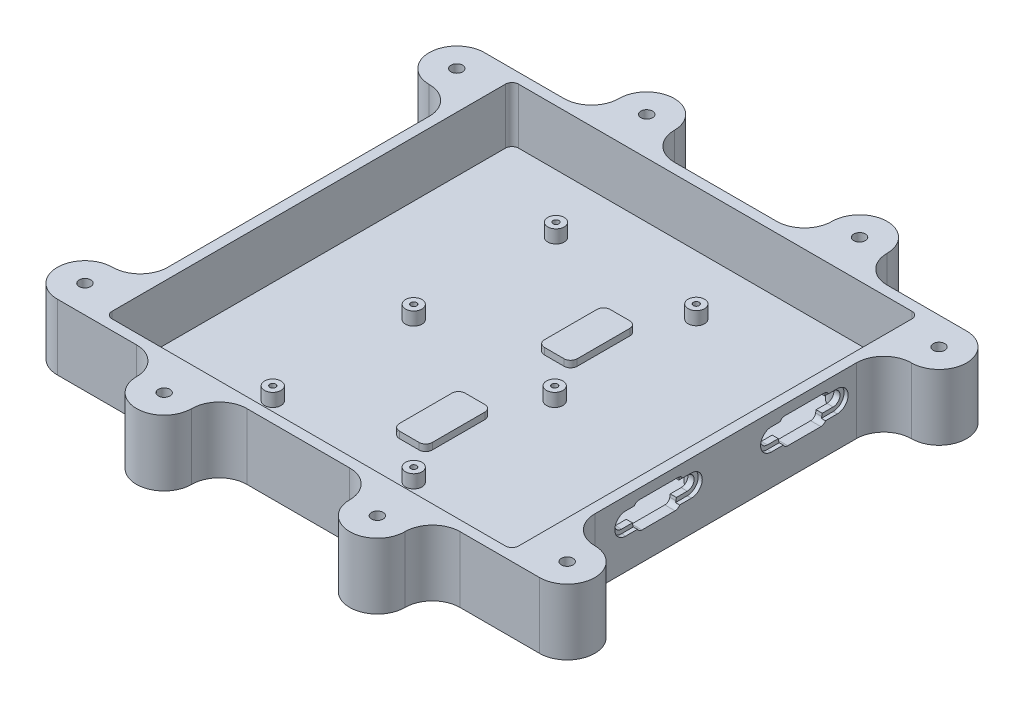
SolidWorks part; units mm, degrees
material "6061-T6 (SS)"
ref_plane "Front Plane" through (0, 0, 0) normal (0, 0, 1) x (1, 0, 0)
ref_plane "Top Plane" through (0, 0, 0) normal (0, 1, 0) x (1, 0, 0)
ref_plane "Right Plane" through (0, 0, 0) normal (1, 0, 0) x (0, 0, -1)
sketch "Sketch1" plane through (0, 0, 0) normal (0, 1, 0) x (1, 0, 0)
  line L1 (0, 0) -> (165.1, 0)
  line L2 (0, 0) -> (0, 165.1)
  line L3 (0, 165.1) -> (165.1, 165.1)
  line L4 (165.1, 0) -> (165.1, 165.1)
  dimension "D1" = 165.1
  dimension "D2" = 165.1
extrude "Boss-Extrude1" add sketch "Sketch1" along normal blind 25.4
shell "Shell1" thickness 3.9624
sketch "Sketch4" plane through (0, 3.9624, 0) normal (0, 1, 0) x (1, 0, 0)
  line L0 (161.1376, 3.9624) -> (161.1376, 161.1376) construction
  line L1 (161.1376, 161.1376) -> (3.9624, 161.1376) construction
  line L2 (161.1376, 161.1376) -> (3.9624, 161.1376) construction
  circle A18 centre (43.5892, 29.022) radius 3.175
  circle A19 centre (98.0872, 29.022) radius 3.175
  circle A20 centre (152.588, 29.022) radius 3.175
  circle A21 centre (152.588, 83.5228) radius 3.175
  circle A22 centre (43.5892, 83.5228) radius 3.175
  circle A23 centre (98.0872, 83.5228) radius 3.175
  circle A24 centre (152.588, 138.2725) radius 3.175
  circle A25 centre (98.0872, 138.2725) radius 3.175
  circle A26 centre (43.5892, 138.524) radius 3.175
  dimension "D4" = 54.7497
  dimension "D5" = 54.5008
  dimension "D7" = 6.35
  dimension "D1" = 8.5496
  dimension "D2" = 22.8651
  dimension "D3" = 109.2505
  dimension "D6" = 108.999
  dimension "D8" = 22.6136
extrude "Boss-Extrude2" add sketch "Sketch4" along normal blind 5.08
fillet "Fillet1" radius 2.54 4 edges at (3.9624, 14.6812, -3.9624) (161.1376, 14.6812, -3.9624) (161.1376, 14.6812, -161.1376) (3.9624, 14.6812, -161.1376)
sketch "Sketch5" plane through (0, 0, 0) normal (0, -1, 0) x (1, 0, 0)
  line L0 (82.55, -165.1) -> (82.55, 0) construction
  line L9 (165.1, -165.1) -> (0, -165.1) construction
  line L10 (0, 0) -> (165.1, 0) construction
  line L19 (175.768, 0) -> (165.1, 0)
  line L20 (-10.668, 0) -> (0, 0)
  line L21 (0, -165.1) -> (0, 0) construction
  line L23 (0, -82.55) -> (44.7871, -82.55) construction
  line L40 (-10.668, -165.1) -> (0, -165.1)
  line L41 (175.768, -165.1) -> (165.1, -165.1)
  line L68 (0, 0) -> (-10.668, 0)
  line L75 (165.1, -165.1) -> (0, -165.1) construction
  line L88 (0, 0) -> (165.1, 0) construction
  line L89 (19.939, 0) -> (62.611, 0)
  line L90 (102.362, 0) -> (145.034, 0)
  line L91 (165.1, 0) -> (165.1, -165.1) construction
  line L92 (165.1, 0) -> (165.1, -32.004)
  line L93 (165.1, -133.096) -> (165.1, -165.1)
  line L94 (145.034, -165.1) -> (102.362, -165.1)
  line L95 (62.738, -165.1) -> (20.066, -165.1)
  line L96 (0, -133.096) -> (0, -165.1)
  line L97 (0, 0) -> (0, -32.004)
  arc A24 (51.943, 10.668) -> (62.611, 0) centre (62.611, 10.668) ccw
  arc A25 (30.607, 10.668) -> (19.939, 0) centre (19.939, 10.668) cw
  arc A26 (51.943, 10.668) -> (41.275, 21.336) centre (41.275, 10.668) ccw
  arc A27 (41.275, 21.336) -> (30.607, 10.668) centre (41.275, 10.668) ccw
  arc A28 (113.03, 10.668) -> (102.362, 0) centre (102.362, 10.668) cw
  arc A29 (134.366, 10.668) -> (145.034, 0) centre (145.034, 10.668) ccw
  arc A30 (134.366, 10.668) -> (123.698, 21.336) centre (123.698, 10.668) ccw
  arc A31 (123.698, 21.336) -> (113.03, 10.668) centre (123.698, 10.668) ccw
  arc A32 (165.1, -32.004) -> (175.768, -21.336) centre (175.768, -32.004) cw
  arc A33 (175.768, -21.336) -> (175.768, 0) centre (175.768, -10.668) ccw
  arc A34 (165.1, -133.096) -> (175.768, -143.764) centre (175.768, -133.096) ccw
  arc A35 (175.768, -143.764) -> (175.768, -165.1) centre (175.768, -154.432) cw
  arc A36 (145.034, -165.1) -> (134.366, -175.768) centre (145.034, -175.768) ccw
  arc A37 (113.03, -175.768) -> (102.362, -165.1) centre (102.362, -175.768) ccw
  arc A38 (134.366, -175.768) -> (113.03, -175.768) centre (123.698, -175.768) cw
  arc A39 (62.738, -165.1) -> (52.07, -175.768) centre (62.738, -175.768) ccw
  arc A40 (30.734, -175.768) -> (20.066, -165.1) centre (20.066, -175.768) ccw
  arc A41 (52.07, -175.768) -> (30.734, -175.768) centre (41.402, -175.768) cw
  arc A42 (0, -133.096) -> (-10.668, -143.764) centre (-10.668, -133.096) cw
  arc A43 (-10.668, -143.764) -> (-10.668, -165.1) centre (-10.668, -154.432) ccw
  arc A44 (0, -32.004) -> (-10.668, -21.336) centre (-10.668, -32.004) ccw
  arc A45 (-10.668, -21.336) -> (-10.668, 0) centre (-10.668, -10.668) cw
  dimension "D5" = 10.668
  dimension "D8" = 41.402
  dimension "D4" = 41.275
  dimension "D9" = 10.668
  dimension "D10" = 10.668
  dimension "D6" = 42.672
  dimension "D13" = 42.672
  dimension "D3" = 10.668
  dimension "D7" = 10.668
  dimension "D14" = 10.668
  dimension "D15" = 10.668
  dimension "D16" = 10.668
  dimension "D18" = 10.668
  dimension "D12" = 10.668
  dimension "D1" = 0
  dimension "D11" = 41.402
  dimension "D17" = 10.668
  dimension "D19" = 10.668
  dimension "D20" = 41.402
  dimension "D21" = 10.668
extrude "Boss-Extrude3" add sketch "Sketch5" against normal blind 25.4
sketch "Sketch25" plane through (0, 3.9624, 0) normal (0, 1, 0) x (1, 0, 0)
  line L0 (0, 82.55) -> (165.1, 82.55) construction
  line L1 (0, 133.096) -> (0, 32.004) construction
  line L2 (165.1, 32.004) -> (165.1, 133.096) construction
ref_plane "Plane1" through (0, 0, -82.55) normal (0, 0, 1) x (1, 0, 0)
sketch "Sketch77" plane through (0, 3.9624, 0) normal (0, 1, 0) x (1, 0, 0)
  line L0 (3.9624, 158.5976) -> (3.9624, 6.5024) construction
  line L1 (78.1787, 66.2508) -> (90.8787, 66.2508)
  line L2 (78.1787, 66.2508) -> (78.1787, 40.8508)
  line L3 (78.1787, 40.8508) -> (90.8787, 40.8508)
  line L4 (90.8787, 66.2508) -> (90.8787, 40.8508)
  line L5 (78.1787, 122.301) -> (90.8787, 122.301)
  line L6 (78.1787, 122.301) -> (78.1787, 96.901)
  line L7 (78.1787, 96.901) -> (90.8787, 96.901)
  line L8 (90.8787, 122.301) -> (90.8787, 96.901)
  line L9 (6.5024, 3.9624) -> (158.5976, 3.9624) construction
  line L10 (158.5976, 161.1376) -> (6.5024, 161.1376) construction
  dimension "D2" = 12.7
  dimension "D3" = 0
  dimension "D4" = 0
  dimension "D5" = 74.2163
  dimension "D6" = 25.4
  dimension "D7" = 38.8366
  dimension "D8" = 30.6502
  dimension "D9" = 36.8884
sketch "Sketch78" [suppressed] plane through (0, 0, 0) normal (0, -1, 0) x (1, 0, 0)
  line L11 (62.484, -165.1) -> (102.362, -165.1)
  line L12 (62.484, -165.1) -> (102.362, -165.1)
  line L13 (145.034, -165.1) -> (175.768, -165.1)
  line L14 (145.034, -165.1) -> (175.768, -165.1)
  line L15 (102.362, 0) -> (62.611, 0)
  line L16 (102.362, 0) -> (62.611, 0)
  line L17 (165.1, -133.096) -> (165.1, -32.004)
  line L18 (19.939, 0) -> (-10.668, 0)
  line L19 (19.939, 0) -> (-10.668, 0)
  line L23 (0, -32.004) -> (0, -133.096)
  line L29 (165.1, -133.096) -> (165.1, -32.004)
  line L35 (0, -32.004) -> (0, -133.096)
  line L54 (-10.668, -165.1) -> (19.812, -165.1)
  line L55 (-10.668, -165.1) -> (19.812, -165.1)
  line L82 (175.768, 0) -> (145.034, 0)
  arc A3 (51.943, 10.668) -> (62.611, 0) centre (62.611, 10.668) ccw
  arc A4 (51.943, 10.668) -> (62.611, 0) centre (62.611, 10.668) ccw
  arc A5 (51.943, 10.668) -> (30.607, 10.668) centre (41.275, 10.668) ccw
  arc A6 (51.943, 10.668) -> (30.607, 10.668) centre (41.275, 10.668) ccw
  arc A7 (19.939, 0) -> (30.607, 10.668) centre (19.939, 10.668) ccw
  arc A8 (19.939, 0) -> (30.607, 10.668) centre (19.939, 10.668) ccw
  arc A32 (-10.668, -143.764) -> (0, -133.096) centre (-10.668, -133.096) ccw
  arc A33 (-10.668, -143.764) -> (0, -133.096) centre (-10.668, -133.096) ccw
  arc A34 (-10.668, -143.764) -> (-10.668, -165.1) centre (-10.668, -154.432) ccw
  arc A35 (-10.668, -143.764) -> (-10.668, -165.1) centre (-10.668, -154.432) ccw
  arc A36 (30.48, -175.768) -> (19.812, -165.1) centre (19.812, -175.768) ccw
  arc A37 (30.48, -175.768) -> (19.812, -165.1) centre (19.812, -175.768) ccw
  arc A38 (30.48, -175.768) -> (51.816, -175.768) centre (41.148, -175.768) ccw
  arc A39 (30.48, -175.768) -> (51.816, -175.768) centre (41.148, -175.768) ccw
  arc A40 (62.484, -165.1) -> (51.816, -175.768) centre (62.484, -175.768) ccw
  arc A41 (62.484, -165.1) -> (51.816, -175.768) centre (62.484, -175.768) ccw
  arc A42 (113.03, -175.768) -> (102.362, -165.1) centre (102.362, -175.768) ccw
  arc A43 (113.03, -175.768) -> (102.362, -165.1) centre (102.362, -175.768) ccw
  arc A44 (113.03, -175.768) -> (134.366, -175.768) centre (123.698, -175.768) ccw
  arc A45 (113.03, -175.768) -> (134.366, -175.768) centre (123.698, -175.768) ccw
  arc A46 (145.034, -165.1) -> (134.366, -175.768) centre (145.034, -175.768) ccw
  arc A47 (145.034, -165.1) -> (134.366, -175.768) centre (145.034, -175.768) ccw
  arc A48 (175.768, -165.1) -> (175.768, -143.764) centre (175.768, -154.432) ccw
  arc A49 (175.768, -165.1) -> (175.768, -143.764) centre (175.768, -154.432) ccw
  arc A50 (165.1, -133.096) -> (175.768, -143.764) centre (175.768, -133.096) ccw
  arc A51 (165.1, -133.096) -> (175.768, -143.764) centre (175.768, -133.096) ccw
  arc A52 (175.768, -21.336) -> (165.1, -32.004) centre (175.768, -32.004) ccw
  arc A53 (175.768, -21.336) -> (165.1, -32.004) centre (175.768, -32.004) ccw
  arc A54 (175.768, -21.336) -> (175.768, 0) centre (175.768, -10.668) ccw
  arc A55 (175.768, -21.336) -> (175.768, 0) centre (175.768, -10.668) ccw
  arc A56 (134.366, 10.668) -> (145.034, 0) centre (145.034, 10.668) ccw
  arc A57 (134.366, 10.668) -> (145.034, 0) centre (145.034, 10.668) ccw
  arc A58 (134.366, 10.668) -> (113.03, 10.668) centre (123.698, 10.668) ccw
  arc A59 (134.366, 10.668) -> (113.03, 10.668) centre (123.698, 10.668) ccw
  arc A60 (102.362, 0) -> (113.03, 10.668) centre (102.362, 10.668) ccw
  arc A61 (102.362, 0) -> (113.03, 10.668) centre (102.362, 10.668) ccw
  arc A62 (-10.668, 0) -> (-10.668, -21.336) centre (-10.668, -10.668) ccw
  arc A63 (-10.668, 0) -> (-10.668, -21.336) centre (-10.668, -10.668) ccw
  arc A64 (0, -32.004) -> (-10.668, -21.336) centre (-10.668, -32.004) ccw
  arc A65 (0, -32.004) -> (-10.668, -21.336) centre (-10.668, -32.004) ccw
  dimension "D1" = 0
extrude "Boss-Extrude5" add sketch "Sketch77" along normal blind 2.54
sketch "Sketch83" [suppressed] plane through (165.1, 0, 0) normal (1, 0, 0) x (0, 0, -1)
  line L0 (43.5089, 25.3323) -> (43.5089, 15.6727) construction
  line L1 (43.5089, 15.6727) -> (68.5102, 15.6727) construction
  line L2 (99.5083, 15.6727) -> (124.5121, 15.6727) construction
  line L3 (106.1085, 12.9891) -> (103.4735, 18.3684)
  line L4 (48.5085, 12.4684) -> (47.4741, 18.3684)
  line L5 (61.9346, 11.1447) -> (50.0845, 11.1447)
  line L6 (64.5449, 18.3684) -> (63.5106, 12.4684)
  line L7 (49.0501, 20.2447) -> (62.969, 20.2447)
  line L12 (31.496, 25.4) -> (133.604, 25.4) construction
  line L14 (31.496, 25.4) -> (31.496, -2.54) construction
  line L15 (116.7542, 11.6654) -> (104.9041, 11.6654)
  line L20 (120.9651, 18.3684) -> (118.3302, 12.9891)
  line L21 (105.0495, 20.2447) -> (119.3892, 20.2447)
  line L22 (31.496, 25.4) -> (133.604, 25.4) construction
  line L23 (143.764, 25.4) -> (143.764, -2.54) construction
  line L24 (133.604, -2.54) -> (31.496, -2.54) construction
  circle A0 centre (43.5089, 15.6727) radius 1.7005
  circle A1 centre (68.5102, 15.6727) radius 1.7005
  arc A4 (48.5085, 12.4684) -> (50.0845, 11.1447) centre (50.0845, 12.7447) ccw
  arc A5 (61.9346, 11.1447) -> (63.5106, 12.4684) centre (61.9346, 12.7447) ccw
  arc A6 (64.5449, 18.3684) -> (62.969, 20.2447) centre (62.969, 18.6447) ccw
  arc A7 (49.0501, 20.2447) -> (47.4741, 18.3684) centre (49.0501, 18.6447) ccw
  circle A18 centre (99.5083, 15.6727) radius 1.7005
  circle A19 centre (124.5121, 15.6727) radius 1.7005
  arc A20 (106.1085, 12.9891) -> (104.9041, 11.6654) centre (106.4873, 11.4346) ccw
  arc A21 (116.7542, 11.6654) -> (118.3302, 12.9891) centre (116.7542, 13.2654) ccw
  arc A22 (120.9651, 18.3684) -> (119.3892, 20.2447) centre (119.3892, 18.6447) ccw
  arc A23 (105.0495, 20.2447) -> (103.4735, 18.3684) centre (105.0495, 18.6447) ccw
  dimension "D3" = 3.4011
  dimension "D4" = 3.4011
  dimension "D9" = 1.6
  dimension "D10" = 1.6
  dimension "D11" = 1.6
  dimension "D12" = 1.6
  dimension "D21" = 3.4011
  dimension "D25" = 1.6
  dimension "D26" = 1.6
  dimension "D27" = 1.6
  dimension "D28" = 1.6
  dimension "D38" = 4.3711
  dimension "D39" = 3.4011
  dimension "D40" = 9.7273
  dimension "D41" = 19.2519
  dimension "D43" = 15.8054
  dimension "D44" = 6.7553
  dimension "D45" = 6.7553
  dimension "D47" = 6.7553
  dimension "D49" = 15.2847
  dimension "D1" = 9.6596
  dimension "D2" = 25.0012
  dimension "D5" = 12.0129
  dimension "D6" = 3.9652
  dimension "D7" = 3.9652
  dimension "D8" = 4.572
  dimension "D13" = 5.99
  dimension "D14" = 5.99
  dimension "D15" = 13.9189
  dimension "D16" = 11.8501
  dimension "D17" = 1.8763
  dimension "D18" = 1.8763
  dimension "D19" = 1.3237
  dimension "D20" = 1.3237
  dimension "D22" = 9.7273
  dimension "D23" = 3.9652
  dimension "D24" = 4.572
  dimension "D29" = 5.99
  dimension "D30" = 5.99
  dimension "D31" = 11.8501
  dimension "D32" = 1.8763
  dimension "D33" = 1.8763
  dimension "D34" = 1.3237
  dimension "D35" = 1.3237
  dimension "D36" = 30.9982
  dimension "D37" = 0
  dimension "D42" = 14.2054
  dimension "D46" = 9.944
  dimension "D48" = 80.056
extrude "Cut-Extrude5" [suppressed] cut sketch "Sketch83" against normal blind 12.7
fillet "Fillet27" radius 2.54 8 edges at (78.1787, 5.2324, -122.301) (90.8787, 5.2324, -122.301) (78.1787, 5.2324, -96.901) (78.1787, 5.2324, -66.2508) (78.1787, 5.2324, -40.8508) (90.8787, 5.2324, -96.901) (90.8787, 5.2324, -66.2508) (90.8787, 5.2324, -40.8508)
hole_wizard "#4-40 Tapped Hole1" positions "Sketch84" profile "Sketch85" tap size "#4-40" standard "ANSI Inch"
sketch "Sketch84" plane through (0, 9.0424, 0) normal (0, 1, 0) x (1, 0, 0)
  point P0 (152.588, 29.022)
  point P3 (152.588, 83.5228)
  point P6 (152.588, 138.2725)
  point P9 (98.0872, 138.2725)
  point P12 (98.0872, 83.5228)
  point P15 (98.0872, 29.022)
  point P18 (43.5892, 29.022)
  point P21 (43.5892, 83.5228)
  point P24 (43.5892, 138.524)
cosmetic thread "Hole Thread1" parameters "D1"=5.588, "D2"=2.8448
cosmetic thread "Hole Thread2" parameters "D1"=5.588, "D2"=2.8448
cosmetic thread "Hole Thread3" parameters "D1"=5.588, "D2"=2.8448
cosmetic thread "Hole Thread4" parameters "D1"=5.588, "D2"=2.8448
cosmetic thread "Hole Thread5" parameters "D1"=5.588, "D2"=2.8448
cosmetic thread "Hole Thread6" parameters "D1"=5.588, "D2"=2.8448
cosmetic thread "Hole Thread7" parameters "D1"=5.588, "D2"=2.8448
cosmetic thread "Hole Thread8" parameters "D1"=5.588, "D2"=2.8448
cosmetic thread "Hole Thread9" parameters "D1"=5.588, "D2"=2.8448
sketch "Sketch85" plane through (152.588, 9.0424, -29.022) normal (1, 0, 0) x (0, 0, 1)
  line L0 (0, 0) -> (0, 7.0292)
  line L1 (0, 7.0292) -> (1.1303, 6.35)
  line L2 (1.1303, 6.35) -> (1.1303, 0)
  line L5 (1.1303, 0) -> (0, 0)
  line L10 (0, 7.0292) -> (-1.1303, 6.35) construction
  line L11 (0, -6.35) -> (0, 107.95) construction
  dimension "Tap Drill Dia." = 2.2606
  dimension "Tap Drill Depth" = 6.35
  dimension "Drill Angle" = 118
sketch "Sketch86" plane through (165.1, 0, 0) normal (1, 0, 0) x (0, 0, -1)
  line L0 (82.55, 25.4) -> (82.55, 0) construction
  line L1 (32.004, 25.4) -> (133.096, 25.4) construction
  line L3 (56.642, 25.4) -> (56.642, 0) construction
  line L4 (50.24, 10.8864) -> (63.044, 10.8864)
  line L6 (64.9626, 12.4963) -> (66.1463, 19.2095)
  line L7 (48.3214, 12.4963) -> (47.1377, 19.2095)
  line L8 (49.0563, 21.496) -> (64.2277, 21.496)
  line L9 (32.004, 0) -> (133.096, 0) construction
  arc A0 (49.0563, 21.496) -> (47.1377, 19.2095) centre (49.0563, 19.5478) ccw
  arc A1 (64.2277, 21.496) -> (66.1463, 19.2095) centre (64.2277, 19.5478) cw
  arc A2 (63.044, 10.8864) -> (64.9626, 12.4963) centre (63.044, 12.8346) ccw
  arc A3 (50.24, 10.8864) -> (48.3214, 12.4963) centre (50.24, 12.8346) cw
  dimension "D3" = 1.9482
  dimension "D1" = 25.908
  dimension "D2" = 6.7132
  dimension "D4" = 10
  dimension "D5" = 15.1714
  dimension "D6" = 10.8864
extrude "Cut-Extrude6" cut sketch "Sketch86" against normal up to surface (3.9624 mm away) up to face at (161.1376, 14.6812, -82.55)
sketch "Sketch87" plane through (165.1, 0, 0) normal (1, 0, 0) x (0, 0, -1)
  line L0 (43.942, 16.1912) -> (69.342, 16.1912) construction
  line L1 (43.942, 18.8582) -> (69.342, 18.8582)
  line L2 (43.942, 13.5242) -> (69.342, 13.5242)
  line L3 (64.2277, 21.496) -> (49.0563, 21.496) construction
  line L4 (50.24, 10.8864) -> (63.044, 10.8864) construction
  line L5 (56.642, 21.496) -> (56.642, 10.8864) construction
  arc A0 (43.942, 18.8582) -> (43.942, 13.5242) centre (43.942, 16.1912) ccw
  arc A1 (69.342, 13.5242) -> (69.342, 18.8582) centre (69.342, 16.1912) ccw
  point P2 (56.642, 16.1912)
  dimension "D1" = 2.667
  dimension "D2" = 25.4
extrude "Cut-Extrude7" cut sketch "Sketch87" against normal up to surface (3.9624 mm away) up to face at (161.1376, 16.0466, -56.642)
sketch "Sketch88" plane through (165.1, 0, 0) normal (1, 0, 0) x (0, 0, -1)
  line L0 (43.942, 16.1912) -> (69.342, 16.1912) construction
  line L1 (43.942, 20.4076) -> (69.342, 20.4076)
  line L2 (43.942, 11.9748) -> (69.342, 11.9748)
  line L3 (47.1997, 18.8582) -> (43.942, 18.8582) construction
  line L4 (43.942, 13.5242) -> (48.1402, 13.5242) construction
  line L5 (56.642, 21.496) -> (56.642, 10.8864) construction
  line L6 (64.2277, 21.496) -> (49.0563, 21.496) construction
  line L7 (50.24, 10.8864) -> (63.044, 10.8864) construction
  arc A0 (43.942, 20.4076) -> (43.942, 11.9748) centre (43.942, 16.1912) ccw
  arc A1 (69.342, 11.9748) -> (69.342, 20.4076) centre (69.342, 16.1912) ccw
  arc A9 (43.942, 18.8582) -> (43.942, 13.5242) centre (43.942, 16.1912) ccw construction
  point P2 (56.642, 16.1912)
  dimension "D1" = 8.4328
extrude "Cut-Extrude8" cut sketch "Sketch88" against normal blind 1.5875
sketch "Sketch91" plane through (165.1, 0, 0) normal (1, 0, 0) x (0, 0, -1)
  line L0 (84.836, 25.4) -> (84.836, 0) construction
  line L1 (32.004, 25.4) -> (133.096, 25.4) construction
  line L2 (32.004, 25.4) -> (32.004, 0) construction
  line L5 (32.004, 0) -> (133.096, 0) construction
  dimension "D1" = 52.832
ref_plane "Plane2" through (0, 0, -84.836) normal (0, 0, 1) x (0, -1, 0)
mirror "Mirror1" about plane through (0, 0, -84.836) normal (0, 0, 1) of "Cut-Extrude7", "Cut-Extrude8", "Cut-Extrude6"
hole_wizard "#8 Clearance Hole1" positions "Sketch95" profile "Sketch96" hole size "#8" standard "ANSI Inch"
sketch "Sketch95" plane through (0, 25.4, 0) normal (0, 1, 0) x (1, 0, 0)
  arc A3 (52.07, 175.768) -> (30.734, 175.768) centre (41.402, 175.768) ccw construction
  arc A4 (134.366, 175.768) -> (113.03, 175.768) centre (123.698, 175.768) ccw construction
  arc A5 (-10.668, 165.1) -> (-10.668, 143.764) centre (-10.668, 154.432) ccw construction
  arc A6 (-10.668, 21.336) -> (-10.668, 0) centre (-10.668, 10.668) ccw construction
  arc A10 (30.607, -10.668) -> (51.943, -10.668) centre (41.275, -10.668) ccw construction
  arc A11 (113.03, -10.668) -> (134.366, -10.668) centre (123.698, -10.668) ccw construction
  arc A12 (175.768, 0) -> (175.768, 21.336) centre (175.768, 10.668) ccw construction
  arc A13 (175.768, 143.764) -> (175.768, 165.1) centre (175.768, 154.432) ccw construction
  point P0 (41.402, 175.768)
  point P2 (123.698, 175.768)
  point P4 (175.768, 154.432)
  point P6 (175.768, 10.668)
  point P8 (123.698, -10.668)
  point P10 (41.275, -10.668)
  point P13 (-10.668, 10.668)
  point P15 (-10.668, 154.432)
sketch "Sketch96" plane through (41.402, 25.4, -175.768) normal (1, 0, 0) x (0, 0, 1)
  line L0 (0, 0) -> (0, 10.2407)
  line L1 (0, 10.2407) -> (2.2479, 8.89)
  line L2 (2.2479, 8.89) -> (2.2479, 0)
  line L5 (2.2479, 0) -> (0, 0)
  line L10 (0, 10.2407) -> (-2.2479, 8.89) construction
  line L11 (0, -6.35) -> (0, 107.95) construction
  dimension "Hole Dia." = 4.4958
  dimension "Hole Depth" = 8.89
  dimension "Drill Angle" = 118
